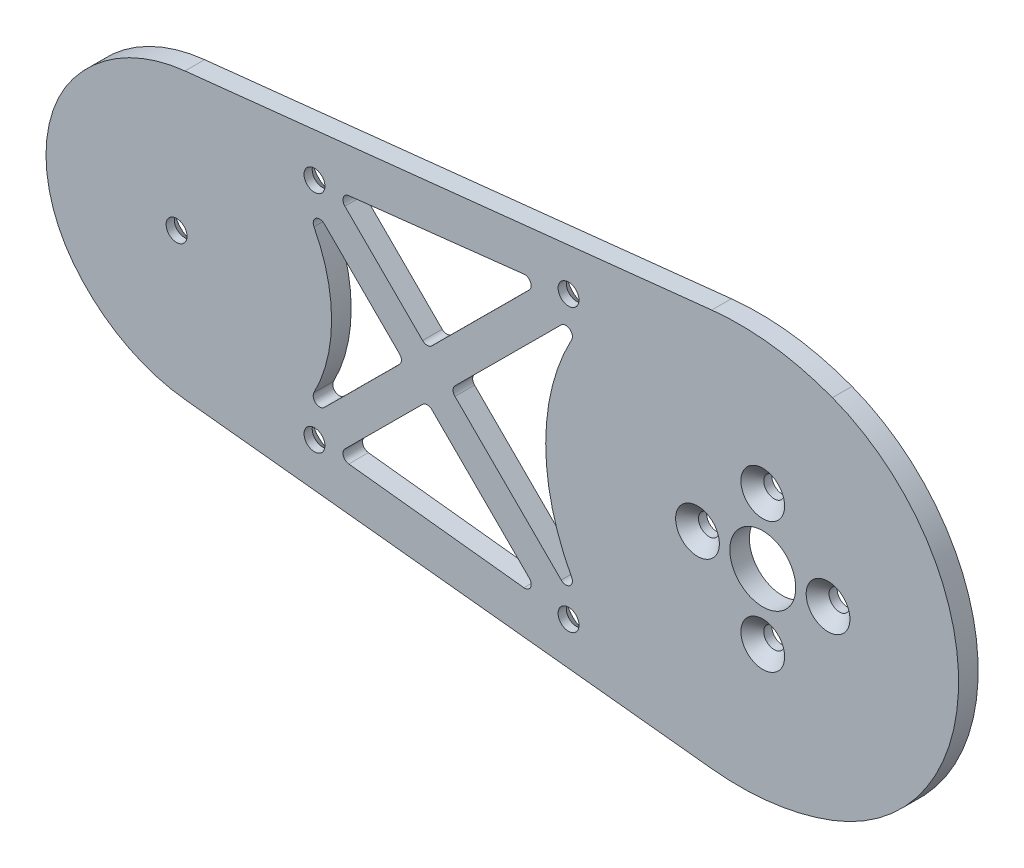
SolidWorks part; units mm, degrees
material "5052-O"
ref_plane "正面" through (0, 0, 0) normal (0, 0, 1) x (1, 0, 0)
ref_plane "平面" through (0, 0, 0) normal (0, 1, 0) x (1, 0, 0)
ref_plane "右側面" through (0, 0, 0) normal (1, 0, 0) x (0, 0, -1)
sketch "ｽｹｯﾁ1" plane through (0, 0, 0) normal (0, 0, 1) x (1, 0, 0)
  line L0 (-2.2272, 19.8756) -> (86.4592, 29.8134)
  line L2 (86.4592, -29.8134) -> (-2.2272, -19.8756)
  line L3 (0, 0) -> (89.8, 0) construction
  arc A0 (-2.2272, 19.8756) -> (-2.2272, -19.8756) centre (0, 0) ccw
  arc A1 (86.4592, -29.8134) -> (86.4592, 29.8134) centre (89.8, 0) ccw
  circle A2 centre (0, 0) radius 1.6
  circle A3 centre (89.8, 0) radius 5.05
  dimension "D1" = 20
  dimension "D2" = 30
  dimension "D4" = 3.2
  dimension "D5" = 10.1
  dimension "D3" = 89.8
extrude "ﾎﾞｽ - 押し出し1" add sketch "ｽｹｯﾁ1" along normal blind 3
sketch "ｽｹｯﾁ2" plane through (0, 0, 3) normal (0, 0, 1) x (1, 0, 0)
  line L0 (89.8, 0) -> (89.8, 10) construction
  line L1 (89.8, 0) -> (99.8, 0) construction
  line L2 (89.8, 0) -> (89.8, -10) construction
  line L3 (89.8, 0) -> (79.8, 0) construction
  circle A0 centre (89.8, 10) radius 1.6
  circle A1 centre (99.8, 0) radius 1.6
  circle A2 centre (89.8, -10) radius 1.6
  circle A3 centre (79.8, 0) radius 1.6
  point P12 (89.8, 0)
  dimension "D2" = 3.2
  dimension "D1" = 10
  dimension "D3" = 4
extrude "ｶｯﾄ - 押し出し1" cut sketch "ｽｹｯﾁ2" against normal through all
sketch "ｽｹｯﾁ3" plane through (0, 0, 3) normal (0, 0, 1) x (1, 0, 0)
  line L0 (86.4592, 29.8134) -> (-2.2272, 19.8756) construction
  line L1 (-2.2272, -19.8756) -> (86.4592, -29.8134) construction
  line L2 (16.8562, -16.7311) -> (64.9784, -22.1235) construction
  line L3 (16.8562, 16.7311) -> (64.9784, 22.1235) construction
  line L4 (21.1278, 17.2098) -> (21.1278, -17.2098) construction
  line L5 (60.0467, 21.5709) -> (60.0467, -21.5709) construction
  line L6 (24.3116, 17.5666) -> (56.0561, 21.1237)
  line L7 (24.3116, -17.5666) -> (56.0561, -21.1237)
  line L8 (21.1278, 17.2098) -> (60.0467, -21.5709) construction
  line L9 (21.1278, -17.2098) -> (60.0467, 21.5709) construction
  line L10 (24.3116, 17.5666) -> (38.399, 3.5293)
  line L11 (38.399, 3.5293) -> (56.0561, 21.1237)
  line L12 (56.0561, -21.1237) -> (38.399, -3.5293)
  line L13 (38.399, -3.5293) -> (24.3116, -17.5666)
  line L14 (22.64, 12.1737) -> (34.8571, 0)
  line L15 (34.8571, 0) -> (22.64, -12.1737)
  line L16 (58.9271, 16.926) -> (41.9408, 0)
  line L17 (41.9408, 0) -> (58.9271, -16.926)
  arc A0 (10.5019, 21.302) -> (10.5019, -21.302) centre (0, 0) cw construction
  arc A1 (72.211, 28.2168) -> (72.211, -28.2168) centre (89.8, 0) ccw construction
  arc A2 (22.1015, 15.9401) -> (22.1015, -15.9401) centre (0, 0) cw construction
  arc A3 (59.136, 20.2554) -> (59.136, -20.2554) centre (89.8, 0) ccw construction
  circle A4 centre (21.1278, 17.2098) radius 1.6
  circle A5 centre (21.1278, -17.2098) radius 1.6
  circle A6 centre (60.0467, -21.5709) radius 1.6
  circle A7 centre (60.0467, 21.5709) radius 1.6
  arc A8 (21.048, 11.0021) -> (21.048, -11.0021) centre (0, 0) cw
  arc A9 (60.5138, 15.7441) -> (60.5138, -15.7441) centre (89.8, 0) ccw
  arc A18 (22.64, 12.1737) -> (21.048, 11.0021) centre (21.9342, 11.4653) ccw
  arc A19 (22.64, -12.1737) -> (21.048, -11.0021) centre (21.9342, -11.4653) cw
  arc A20 (58.9271, 16.926) -> (60.5138, 15.7441) centre (59.633, 16.2177) cw
  arc A21 (58.9271, -16.926) -> (60.5138, -15.7441) centre (59.633, -16.2177) ccw
  circle A22 centre (21.1278, 17.2098) radius 3 construction
  dimension "D1" = 23.75
  dimension "D2" = 33.25
  dimension "D3" = 3.5
  dimension "D4" = 3.5
  dimension "D7" = 3.2
  dimension "D8" = 2.5
  dimension "D9" = 5
  dimension "D12" = 1
  dimension "D13" = 6
  dimension "D5" = 5.25
  dimension "D6" = 5.25
  dimension "D10" = 5
  dimension "D11" = 5
extrude "ｶｯﾄ - 押し出し2" cut sketch "ｽｹｯﾁ3" against normal through all
fillet "ﾌｨﾚｯﾄ1" radius 1 8 edges at (56.0561, -21.1237, 1.5) (24.3116, -17.5666, 1.5) (38.399, -3.5293, 1.5) (56.0561, 21.1237, 1.5) (24.3116, 17.5666, 1.5) (38.399, 3.5293, 1.5) (41.9408, 0, 1.5) (34.8571, 0, 1.5)
sketch "ｽｹｯﾁ4" plane through (0, 0, 3) normal (0, 0, 1) x (1, 0, 0)
  line L0 (-2.3694, 22.1537) -> (86.415, 31.6495) construction
  line L1 (0, 0) -> (89.8, 0) construction
  line L2 (86.415, -31.6495) -> (-2.3694, -22.1537) construction
  line L3 (-2.6092, 24.3959) -> (86.1751, 33.8917) construction
  line L4 (86.1751, -33.8917) -> (-2.6092, -24.3959) construction
  line L5 (1.2941, 21.7962) -> (81.9897, 30.4269)
  line L6 (86.4592, 29.8134) -> (-2.2272, 19.8756) construction
  line L7 (86.4592, 29.8134) -> (-2.2272, 19.8756)
  line L8 (1.2941, -21.7962) -> (81.9897, -30.4269)
  line L9 (86.4592, -29.8134) -> (-2.2272, -19.8756)
  arc A0 (86.415, 31.6495) -> (86.415, -31.6495) centre (89.8, 0) cw construction
  arc A1 (-2.3694, 22.1537) -> (-2.3694, -22.1537) centre (0, 0) ccw construction
  arc A2 (81.9897, 30.4269) -> (100.4693, 28.0387) centre (86.2436, -9.3462) cw
  circle A3 centre (89.8, 0) radius 5.05 construction
  arc A4 (86.1751, 33.8917) -> (86.1751, -33.8917) centre (89.8, 0) cw construction
  arc A5 (-2.6092, 24.3959) -> (-2.6092, -24.3959) centre (0, 0) ccw construction
  arc A6 (1.2941, 21.7962) -> (-15.811, 12.248) centre (3.9527, -3.062) ccw
  arc A7 (-2.2272, 19.8756) -> (-2.2272, -19.8756) centre (0, 0) ccw construction
  arc A8 (86.4592, -29.8134) -> (86.4592, 29.8134) centre (89.8, 0) ccw construction
  arc A9 (-15.811, 12.248) -> (-2.2272, 19.8756) centre (0, 0) cw
  arc A10 (86.4592, 29.8134) -> (100.4693, 28.0387) centre (89.8, 0) cw
  arc A11 (81.9897, -30.4269) -> (100.4693, -28.0387) centre (86.2436, 9.3462) ccw
  arc A12 (86.4592, -29.8134) -> (100.4693, -28.0387) centre (89.8, 0) ccw
  arc A13 (1.2941, -21.7962) -> (-15.811, -12.248) centre (3.9527, 3.062) cw
  arc A14 (-15.811, -12.248) -> (-2.2272, -19.8756) centre (0, 0) ccw
  arc M49 (86.4592, -29.8134) -> (86.4592, 29.8134) centre (89.8, 0) ccw
  line M50 (86.4592, 29.8134) -> (-2.2272, 19.8756)
  arc M51 (-2.2272, 19.8756) -> (-2.2272, -19.8756) centre (0, 0) ccw
  line M52 (-2.2272, -19.8756) -> (86.4592, -29.8134)
  dimension "D1" = 22.28
  dimension "D2" = 31.83
  dimension "D5" = 25
  dimension "D6" = 40
  dimension "D4" = 6
  dimension "D3" = 2.255
extrude "ﾎﾞｽ - 押し出し2" add sketch "ｽｹｯﾁ4" against normal up to surface (3 mm away) contours L5 A6 A2 M51 M50 M49 | A13 L8 A11 M49 M52 M51 up to face at (22.7278, -17.2098, 0)
chamfer "面取り1" distance 1.75 angle 45 5 edges at (22.7278, 17.2098, 0) (22.7278, -17.2098, 0) (61.6467, -21.5709, 0) (61.6467, 21.5709, 0) (1.6, 0, 0)
chamfer "面取り2" distance 1.75 angle 45 4 edges at (91.4, -10, 3) (81.4, 0, 3) (91.4, 10, 3) (101.4, 0, 3)
